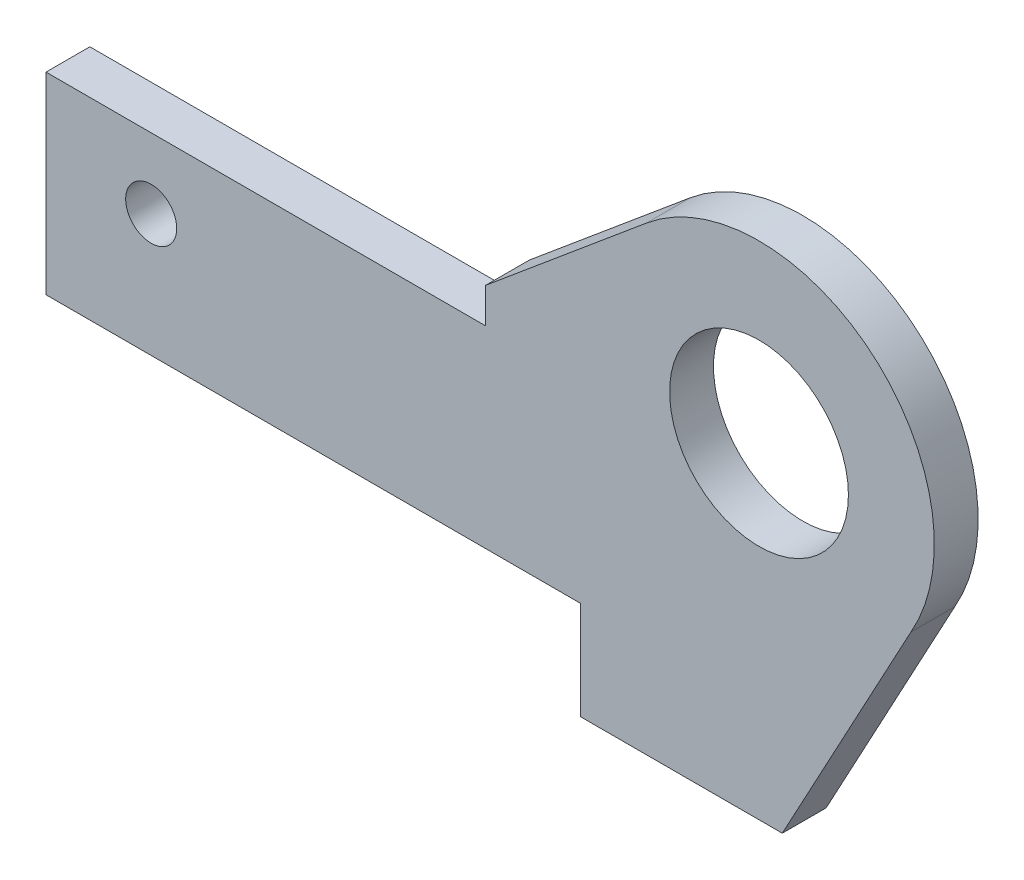
SolidWorks part; units mm, degrees
ref_plane "Front Plane" through (0, 0, 0) normal (0, 0, 1) x (1, 0, 0)
ref_plane "Top Plane" through (0, 0, 0) normal (0, 1, 0) x (1, 0, 0)
ref_plane "Right Plane" through (0, 0, 0) normal (1, 0, 0) x (0, 0, -1)
sketch "Sketch1" plane through (0, 0, 0) normal (0, 0, 1) x (1, 0, 0)
  line L0 (0, 59.8998) -> (0, -63.9034) construction
  line L1 (-91.0361, 0) -> (94.0527, 0) construction
  line L2 (-19.812, 0) -> (-19.812, -2.54)
  line L3 (-19.812, -2.54) -> (-28.7909, -2.54)
  line L4 (-19.812, 0) -> (-8.141, 9.7475)
  line L5 (0, -12.7) -> (-28.7909, -12.7)
  line L6 (-28.7909, -2.54) -> (-28.7909, -12.7)
  line L7 (-19.812, 0) -> (-19.812, -12.7) construction
  line L8 (-19.812, -63.5) -> (10.9985, -6.35)
  line L9 (-28.7909, -12.7) -> (-19.812, -12.7)
  line L10 (-28.7909, -12.7) -> (-28.7909, -63.5)
  line L11 (-28.7909, -63.5) -> (-19.812, -63.5)
  line L12 (-19.812, -12.7) -> (-19.812, -63.5)
  line L13 (0, 0) -> (10.9985, -6.35) construction
  circle A0 centre (0, 0) radius 6.477
  circle A1 centre (0, 0) radius 12.7
  point P7 (-19.812, -2.54)
  dimension "D1" = 12.954
  dimension "D4" = 25.4
  dimension "D2" = 19.812
  dimension "D3" = 2.54
  dimension "D5" = 8.9789
  dimension "D6" = 0
  dimension "D7" = 50.8
  dimension "D8" = 30
extrude "Boss-Extrude1" add sketch "Sketch1" along normal blind 3.175 contours A1 L4 L2 L3 L6 L5 | A0 | L12 L5 L9 L10 L11 | A1 L5 L12 L8
sketch "Sketch2" plane through (0, 0, 3.175) normal (0, 0, 1) x (1, 0, 0)
  line L0 (-28.7909, -2.54) -> (-28.7909, -63.5) construction
  line L1 (-28.7909, -63.5) -> (7.7535, -63.5)
  line L2 (-28.7909, -63.5) -> (-28.7909, -23.622)
  line L3 (-28.7909, -23.622) -> (7.7535, -23.622)
  line L4 (7.7535, -63.5) -> (7.7535, -23.622)
  line L5 (-28.7909, -63.5) -> (-19.812, -63.5) construction
  line L6 (-19.812, -2.54) -> (-28.7909, -2.54) construction
  dimension "D1" = 21.082
extrude "Cut-Extrude1" cut sketch "Sketch2" against normal up to next
sketch "Sketch3" plane through (-28.7909, 0, 0) normal (-1, 0, 0) x (0, 0, 1)
  line L0 (3.175, -2.54) -> (3.175, -23.622) construction
  line L1 (0, -2.54) -> (3.175, -2.54)
  line L2 (0, -2.54) -> (0, -16.51)
  line L3 (0, -16.51) -> (3.175, -16.51)
  line L4 (3.175, -2.54) -> (3.175, -16.51)
  dimension "D1" = 13.97
extrude "Boss-Extrude2" add sketch "Sketch3" along normal blind 22.86
sketch "Sketch4" plane through (0, 0, 0) normal (0, 0, -1) x (-1, 0, 0)
  line L2 (51.6509, -16.51) -> (28.7909, -16.51) construction
  line L3 (51.6509, -2.54) -> (51.6509, -16.51) construction
  circle A0 centre (44.0309, -7.62) radius 3.1992
  dimension "D1" = 8.89
  dimension "D2" = 7.62
hole_wizard "M3 Clearance Hole1" positions "Sketch5" profile "Sketch6" hole size "M3" standard "ANSI Metric"
sketch "Sketch5" plane through (0, 0, 0) normal (0, 0, -1) x (-1, 0, 0)
  point P0 (44.0309, -7.62)
sketch "Sketch6" plane through (-44.0309, -7.62, 0) normal (1, 0, 0) x (0, 1, 0)
  line L0 (0, 0) -> (0, 26.5116)
  line L1 (0, 26.5116) -> (1.85, 25.4)
  line L2 (1.85, 25.4) -> (1.85, 0)
  line L5 (1.85, 0) -> (0, 0)
  line L10 (0, 26.5116) -> (-1.85, 25.4) construction
  line L11 (0, -6.35) -> (0, 107.95) construction
  dimension "Hole Dia." = 3.7
  dimension "Hole Depth" = 25.4
  dimension "Drill Angle" = 118
sketch "Sketch7" plane through (-28.7909, 0, 0) normal (-1, 0, 0) x (0, 0, 1)
  line L1 (0, -16.51) -> (3.175, -16.51)
  line L2 (0, -16.51) -> (0, -23.622)
  line L3 (0, -23.622) -> (3.175, -23.622)
  line L4 (3.175, -16.51) -> (3.175, -23.622)
extrude "Cut-Extrude2" cut sketch "Sketch7" against normal blind 15.875
